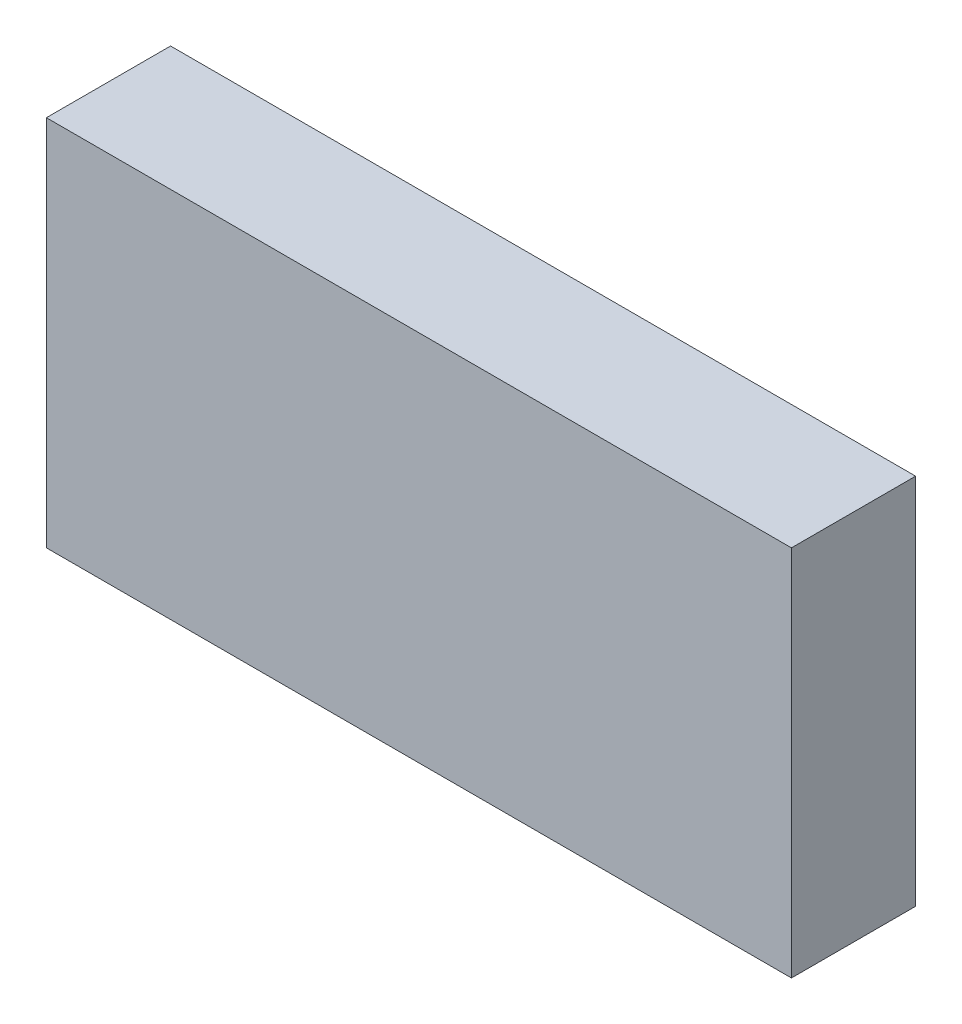
SolidWorks part; units mm, degrees
ref_plane "Front Plane" through (0, 0, 0) normal (0, 0, 1) x (1, 0, 0)
ref_plane "Top Plane" through (0, 0, 0) normal (0, 1, 0) x (1, 0, 0)
ref_plane "Right Plane" through (0, 0, 0) normal (1, 0, 0) x (0, 0, -1)
sketch "Sketch2" plane through (0, 0, 0) normal (0, 0, 1) x (1, 0, 0)
  line L1 (-9.525, 4.7625) -> (9.525, 4.7625)
  line L2 (-9.525, 4.7625) -> (-9.525, -4.7625)
  line L3 (-9.525, -4.7625) -> (9.525, -4.7625)
  line L4 (9.525, 4.7625) -> (9.525, -4.7625)
  line L5 (-9.525, 4.7625) -> (9.525, -4.7625) construction
  line L6 (-9.525, -4.7625) -> (9.525, 4.7625) construction
  point P0 (0, 0)
  dimension "D1" = 19.05
  dimension "D2" = 9.525
extrude "Boss-Extrude1" add sketch "Sketch2" along normal blind 3.175
